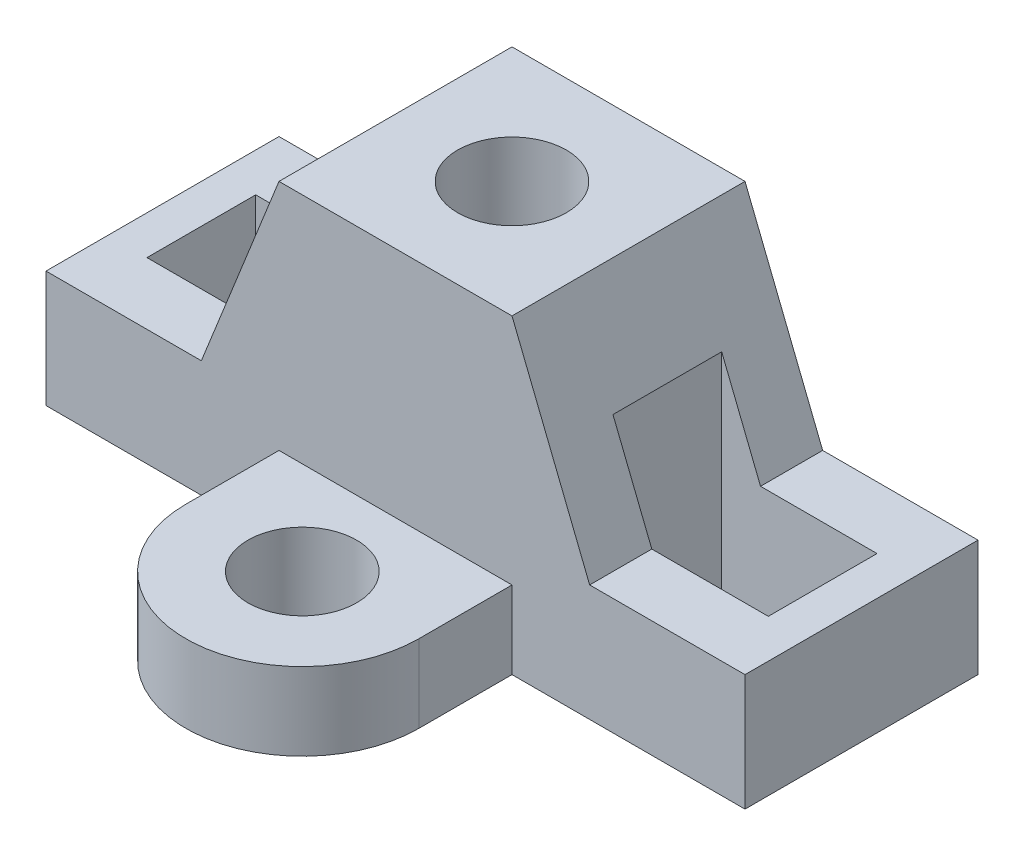
SolidWorks part; units mm, degrees
ref_plane "Front Plane" through (0, 0, 0) normal (0, 0, 1) x (1, 0, 0)
ref_plane "Top Plane" through (0, 0, 0) normal (0, 1, 0) x (1, 0, 0)
ref_plane "Right Plane" through (0, 0, 0) normal (1, 0, 0) x (0, 0, -1)
sketch "Sketch2" plane through (0, 0, 0) normal (0, 0, 1) x (1, 0, 0)
  line L0 (-45, 0) -> (45, 0)
  line L1 (45, 0) -> (45, 15)
  line L2 (45, 15) -> (25, 15)
  line L3 (25, 15) -> (15, 40)
  line L4 (15, 40) -> (-15, 40)
  line L5 (-15, 40) -> (-25, 15)
  line L6 (-25, 15) -> (-45, 15)
  line L7 (-45, 15) -> (-45, 0)
  line L8 (0, 0) -> (0, 59.9267) construction
  point P4 (0, 0)
  point P12 (0, 40)
  dimension "D1" = 90
  dimension "D2" = 15
  dimension "D3" = 30
  dimension "D4" = 20
  dimension "D5" = 20
  dimension "D6" = 40
extrude "Boss-Extrude1" add sketch "Sketch2" against normal blind 30
sketch "Sketch3" plane through (0, 0, 0) normal (0, 1, 0) x (1, 0, 0)
  line L0 (-40, 22) -> (-20, 22)
  line L1 (-20, 22) -> (-20, 8)
  line L2 (-20, 8) -> (-40, 8)
  line L3 (-40, 8) -> (-40, 22)
  line L4 (-45, 30) -> (-45, 0) construction
  line L5 (-25, 30) -> (-45, 30) construction
  line L6 (0, 0) -> (0, 40.3763) construction
  line L7 (20, 22) -> (20, 8)
  line L8 (20, 8) -> (40, 8)
  line L9 (40, 8) -> (40, 22)
  line L10 (40, 22) -> (20, 22)
  point P4 (-40, 15)
  point P7 (-30, 22)
  dimension "D1" = 20
  dimension "D2" = 5
  dimension "D3" = 14
  dimension "D4" = 8
extrude "Cut-Extrude1" cut sketch "Sketch3" against normal through all both and the other way through all
sketch "Sketch4" plane through (0, 0, 0) normal (0, 1, 0) x (1, 0, 0)
  circle A0 centre (0, 15) radius 7
  dimension "D1" = 14
  dimension "D2" = 15
extrude "Cut-Extrude2" cut sketch "Sketch4" along normal through all both and the other way through all
sketch "Sketch5" plane through (0, 0, 0) normal (0, 1, 0) x (1, 0, 0)
  line L0 (-15, 0) -> (-15, -12)
  line L1 (15, 0) -> (-15, 0) construction
  line L2 (15, 0) -> (15, -12)
  line L3 (-15, 0) -> (15, 0)
  arc A0 (-15, -12) -> (15, -12) centre (0, -12) ccw
  circle A1 centre (0, -12) radius 7
  point P7 (0, 0)
  dimension "D2" = 15
  dimension "D3" = 14
  dimension "D1" = 12
extrude "Boss-Extrude3" add sketch "Sketch5" along normal blind 10
